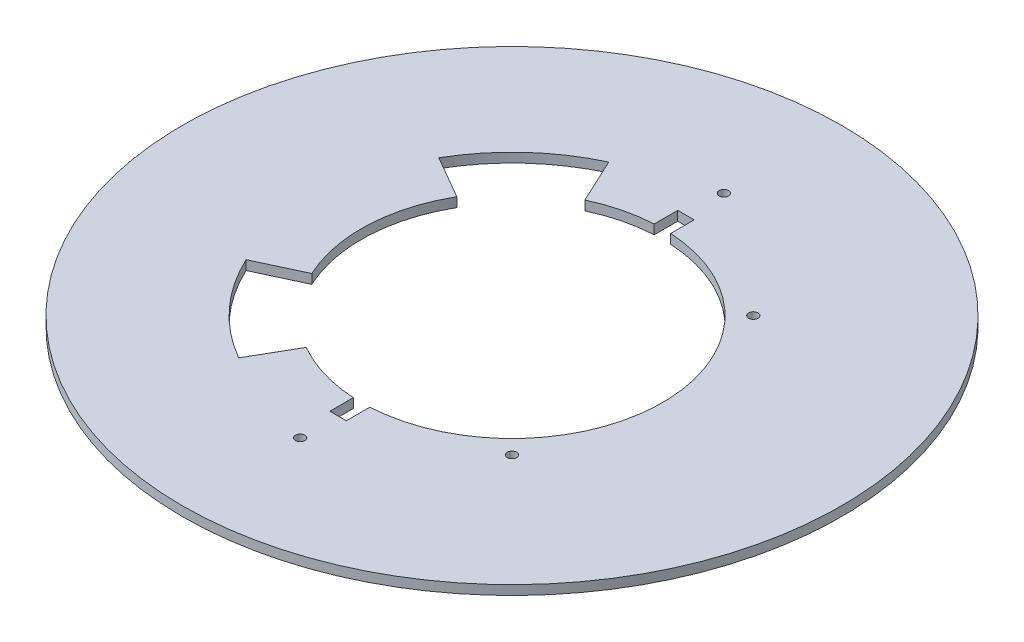
SolidWorks part; units mm, degrees
ref_plane "Front Plane" through (0, 0, 0) normal (0, 0, 1) x (1, 0, 0)
ref_plane "Top Plane" through (0, 0, 0) normal (0, 1, 0) x (1, 0, 0)
ref_plane "Right Plane" through (0, 0, 0) normal (1, 0, 0) x (0, 0, -1)
sketch "Sketch1" plane through (0, 0, 0) normal (0, 1, 0) x (1, 0, 0)
  circle A0 centre (0, 0) radius 64
  circle A1 centre (0, 0) radius 140
  dimension "D1" = 128
  dimension "D2" = 280
extrude "Boss-Extrude1" add sketch "Sketch1" along normal mid plane 4
sketch "Sketch2" plane through (0, 2, 0) normal (0, 1, 0) x (1, 0, 0)
  line L0 (0, 0) -> (0, 64) construction
  line L1 (0, 0) -> (0, -64) construction
  line L2 (0, 64) -> (0, 73.9042) construction
  line L3 (-3.5, 73.9042) -> (0, 73.9042)
  line L4 (0, 73.9042) -> (3.5, 73.9042)
  line L5 (-3.5, 73.9042) -> (-3.5, 63.9042)
  line L6 (3.5, 73.9042) -> (3.5, 63.9042)
  line L7 (-64, 0) -> (64, 0) construction
  line L8 (0, -64) -> (0, -73.9042) construction
  line L9 (3.5, -73.9042) -> (3.5, -63.9042)
  line L10 (-3.5, -73.9042) -> (-3.5, -63.9042)
  line L11 (0, -73.9042) -> (3.5, -73.9042)
  line L12 (-3.5, -73.9042) -> (0, -73.9042)
  circle A0 centre (0, 0) radius 64 construction
  circle A1 centre (0, 0) radius 64 construction
  arc A2 (-3.5, 63.9042) -> (3.5, 63.9042) centre (0, 0) cw
  arc A3 (-3.5, -63.9042) -> (3.5, -63.9042) centre (0, 0) ccw
  dimension "D1" = 10
  dimension "D2" = 7
extrude "Cut-Extrude1" cut sketch "Sketch2" against normal through all
sketch "Sketch3" plane through (0, 2, 0) normal (0, 1, 0) x (1, 0, 0)
  line L0 (-64, 0) -> (64, 0) construction
  line L1 (0, 0) -> (0, 140) construction
  line L2 (0, 0) -> (0, -140) construction
  line L3 (64, 0) -> (140, 0) construction
  line L4 (-64, 0) -> (-140, 0) construction
  line L5 (98.9949, -98.9949) -> (0, 0) construction
  line L6 (0, 0) -> (-98.9949, 98.9949) construction
  line L7 (0, 0) -> (98.9949, 98.9949) construction
  line L8 (0, 0) -> (-98.9949, -98.9949) construction
  arc A0 (-3.5, 63.9042) -> (-3.5, -63.9042) centre (0, 0) ccw construction
  arc A1 (3.5, -63.9042) -> (3.5, 63.9042) centre (0, 0) ccw construction
  circle A2 centre (0, 0) radius 140 construction
  circle A3 centre (0, 0) radius 130 construction
  circle A4 centre (0, 0) radius 130 construction
  circle A5 centre (0, 0) radius 95 construction
  point P18 (-130, 0)
  point P19 (130, 0)
  point P20 (0, -130)
  point P21 (0, 130)
  point P24 (91.9239, -91.9239)
  point P28 (-91.9239, 91.9239)
  point P29 (-91.9239, -91.9239)
  point P30 (-91.9239, 91.9239)
  point P31 (91.9239, 91.9239)
  point P32 (91.9239, -91.9239)
  point P33 (91.9239, 91.9239)
  point P34 (-91.9239, -91.9239)
  point P36 (130, 0)
  point P37 (0, 130)
  point P38 (0, -130)
  point P39 (-130, 0)
  point P40 (-67.1751, 67.1751)
  point P41 (-67.1751, -67.1751)
  point P42 (67.1751, -67.1751)
  point P43 (67.1751, 67.1751)
  dimension "D1" = 260
  dimension "D2" = 10
  dimension "D4" = 190
  dimension "D3" = 45
sketch "Sketch4" plane through (0, 2, 0) normal (0, 1, 0) x (1, 0, 0)
  line L0 (0, 0) -> (-98.9949, 98.9949) construction
  line L1 (98.9949, 98.9949) -> (-98.9949, -98.9949) construction
  circle A0 centre (-51.2652, 51.2652) radius 2
  circle A1 centre (51.2652, -51.2652) radius 2
  dimension "D1" = 4
  dimension "D2" = 145
extrude "Cut-Extrude2" cut sketch "Sketch4" against normal through all
sketch "Sketch5" plane through (0, 2, 0) normal (0, 1, 0) x (1, 0, 0)
  line L0 (-64, 0) -> (64, 0) construction
  line L1 (0, 0) -> (0, -140) construction
  circle A0 centre (0, -90) radius 2
  circle A1 centre (0, 90) radius 2
  dimension "D1" = 4
  dimension "D2" = 180
extrude "Cut-Extrude3" cut sketch "Sketch5" against normal through all
sketch "Sketch6" plane through (0, 2, 0) normal (0, 1, 0) x (1, 0, 0)
  line L0 (0, 0) -> (-98.9949, -98.9949) construction
  line L1 (-98.9949, 98.9949) -> (98.9949, -98.9949) construction
  circle A0 centre (-51.2652, -51.2652) radius 2
  circle A1 centre (51.2652, 51.2652) radius 2
  dimension "D1" = 4
  dimension "D2" = 145
extrude "Cut-Extrude4" cut sketch "Sketch6" against normal through all
sketch "Sketch7" plane through (0, 2, 0) normal (0, 1, 0) x (1, 0, 0)
  line L2 (0, 0) -> (-45.2548, -45.2548) construction
  line L3 (0, 0) -> (0, 64) construction
  line L4 (0, 0) -> (0, -64) construction
  line L5 (0, 0) -> (-64, 0) construction
  line L6 (0, 0) -> (64, 0) construction
  line L7 (0, 0) -> (45.2548, -45.2548) construction
  line L8 (0, 0) -> (-60.1041, 60.1041) construction
  line L9 (0, 0) -> (-27.0476, 58.0037) construction
  line L10 (0, 0) -> (-55.4256, 32) construction
  line L11 (-27.0476, 58.0037) -> (-35.9226, 77.0362)
  line L12 (-55.4256, 32) -> (-73.6122, 42.5)
  line L13 (-45.2548, -45.2548) -> (-60.1041, -60.1041) construction
  line L14 (0, 0) -> (-58.0037, -27.0476) construction
  line L15 (0, 0) -> (-32, -55.4256) construction
  line L16 (-58.0037, -27.0476) -> (-77.0362, -35.9226)
  line L17 (-32, -55.4256) -> (-42.5, -73.6122)
  circle A0 centre (0, 0) radius 64 construction
  circle A1 centre (0, 0) radius 85 construction
  arc A4 (-55.4256, 32) -> (-27.0476, 58.0037) centre (0, 0) cw
  arc A5 (-73.6122, 42.5) -> (-35.9226, 77.0362) centre (0, 0) cw
  arc A6 (-32, -55.4256) -> (-58.0037, -27.0476) centre (0, 0) cw
  arc A7 (-42.5, -73.6122) -> (-77.0362, -35.9226) centre (0, 0) cw
  point P24 (-45.2548, 45.2548)
  dimension "D1" = 170
  dimension "D2" = 45
  dimension "D3" = 20
  dimension "D4" = 15
  dimension "D6" = 20
  dimension "D7" = 15
  dimension "D8" = 45
extrude "Cut-Extrude6" cut sketch "Sketch7" against normal through all
